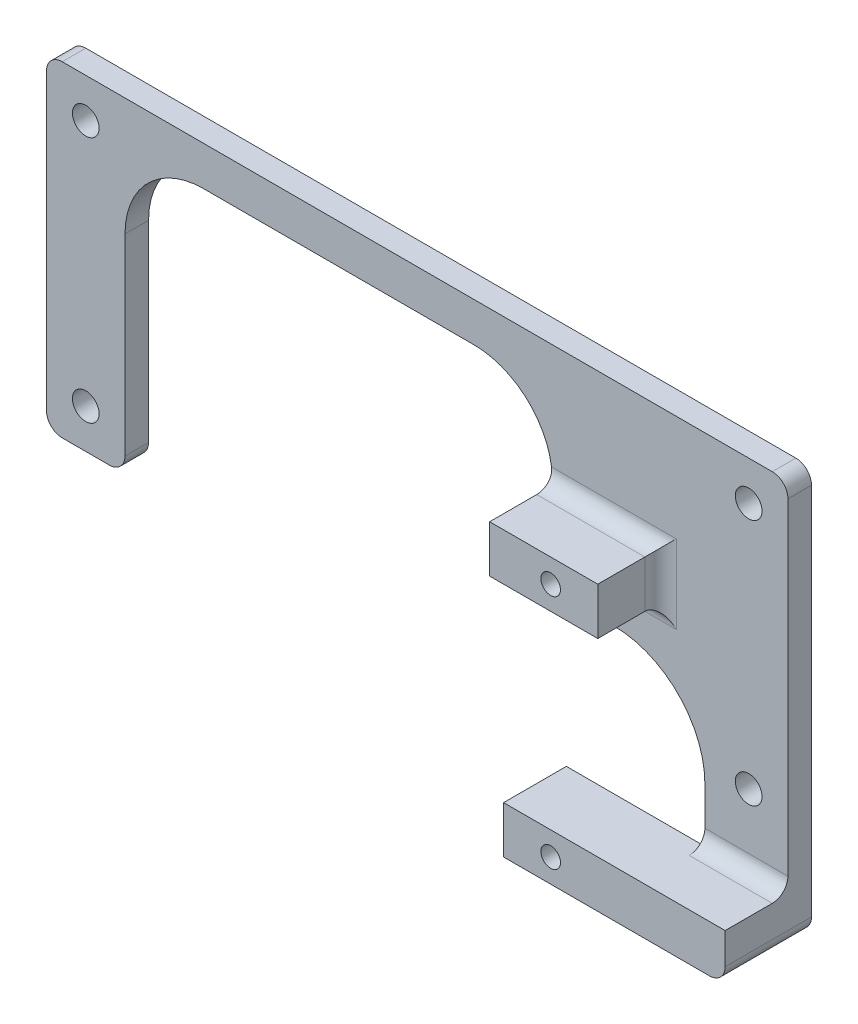
SolidWorks part; units mm, degrees
ref_plane "Front Plane" through (0, 0, 0) normal (0, 0, 1) x (1, 0, 0)
ref_plane "Top Plane" through (0, 0, 0) normal (0, 1, 0) x (1, 0, 0)
ref_plane "Right Plane" through (0, 0, 0) normal (1, 0, 0) x (0, 0, -1)
sketch "Sketch1" plane through (0, 0, 0) normal (0, 0, 1) x (1, 0, 0)
  line L0 (23.4746, -31.0442) -> (23.4746, 7.8468)
  line L1 (-40.9754, 12.8468) -> (53.4746, 12.8468)
  line L2 (-40.9754, 12.8468) -> (-40.9754, -28.6532)
  line L3 (-40.9754, -28.6532) -> (53.4746, -28.6532)
  line L4 (53.4746, 12.8468) -> (53.4746, -28.6532)
  line L5 (23.4746, -31.0442) -> (-30.9754, -31.0442)
  line L6 (23.4746, 7.8468) -> (-30.9754, 7.8468)
  line L7 (-30.9754, -31.0442) -> (-30.9754, 7.8468)
  line L8 (23.4746, -31.0442) -> (-30.9754, 7.8468) construction
  line L9 (23.4746, 7.8468) -> (-30.9754, -31.0442) construction
  line L10 (53.4746, 10.8468) -> (53.4746, -26.6532) construction
  line L11 (-40.9754, -26.6532) -> (-40.9754, 10.8468) construction
  point P5 (-3.7504, -11.5987)
  dimension "D1" = 0
  dimension "D2" = 41.5
  dimension "D3" = 5
  dimension "D4" = 30
  dimension "D5" = 10
  dimension "D6" = 0
extrude "Boss-Extrude1" add sketch "Sketch1" along normal blind 3 contours L3 L7 L6 L0 L4 L1 L2
fillet "Fillet1" radius 10 2 edges at (23.4746, 7.8468, 1.5) (-30.9754, 7.8468, 1.5)
sketch "Sketch2" plane through (0, 0, 0) normal (0, 0, -1) x (-1, 0, 0)
  line L0 (40.9754, 12.8468) -> (40.9754, -28.6532) construction
  line L1 (-53.4746, 12.8468) -> (-53.4746, -28.6532) construction
  line L2 (40.9754, 12.8468) -> (-53.4746, 12.8468) construction
  line L3 (-53.4746, 12.8468) -> (-53.4746, -28.6532) construction
  line L4 (-23.4746, -28.6532) -> (-53.4746, -28.6532) construction
  point P0 (-48.4746, 7.8468)
  point P1 (35.9754, -23.6532)
  point P4 (-48.4746, -23.6532)
  point P11 (35.9754, 7.8468)
  dimension "D1" = 5
  dimension "D2" = 5
  dimension "D3" = 5
  dimension "D4" = 5
  dimension "D5" = 5
  dimension "D6" = 5
  dimension "D7" = 5
  dimension "D8" = 5
hole_wizard "M3 Clearance Hole1" positions "Sketch3" profile "Sketch4" hole size "M3" standard "ANSI Metric" end condition through all
sketch "Sketch3" plane through (0, 0, 0) normal (0, 0, -1) x (-1, 0, 0)
  point P0 (-48.4746, 7.8468)
  point P6 (35.9754, -23.6532)
  point P9 (35.9754, 7.8468)
  point P17 (-48.4746, -23.6532)
  point P20 (-29.4675, -37.9659)
  point P22 (-48.4746, -23.6532)
  point P24 (-48.4746, -23.6532)
sketch "Sketch4" plane through (48.4746, 7.8468, 0) normal (1, 0, 0) x (0, 1, 0)
  line L0 (0, 0) -> (0, 3)
  line L1 (0, 3) -> (1.7, 3)
  line L2 (1.7, 3) -> (1.7, 0)
  line L5 (1.7, 0) -> (0, 0)
  line L11 (0, -6.35) -> (0, 107.95) construction
  dimension "Thru Hole Dia." = 3.4
  dimension "Thru Hole Depth" = 3
sketch "Sketch5" plane through (0, 0, 3) normal (0, 0, 1) x (1, 0, 0)
  line L4 (31.2496, -14.2567) -> (23.4746, -14.2567)
  line L5 (23.4746, -28.6532) -> (23.4746, -2.1532) construction
  line L6 (23.4746, -14.2567) -> (23.4746, -17.232)
  line L9 (42.896, -25.9032) -> (42.896, -28.6532)
  line L10 (23.4746, -28.6532) -> (53.4746, -28.6532) construction
  line L11 (42.896, -28.6532) -> (42.5667, -28.6532)
  circle A1 centre (31.2496, -25.9032) radius 11.6464
  circle A3 centre (6.2496, -7.9032) radius 6.35 construction
  point P0 (31.2496, -25.9032)
  dimension "D1" = 25
  dimension "D2" = 18
extrude "Cut-Extrude1" cut sketch "Sketch5" against normal through all
sketch "Sketch7" plane through (0, 0, 3) normal (0, 0, 1) x (1, 0, 0)
  line L0 (37.2496, -4.7282) -> (37.2496, -9.2282) construction
  line L1 (23.4746, -2.6782) -> (37.2496, -2.6782)
  line L2 (23.4746, -2.6782) -> (23.4746, -8.6782)
  line L3 (23.4746, -8.6782) -> (37.2496, -8.6782)
  line L4 (37.2496, -2.6782) -> (37.2496, -8.6782)
  line L5 (25.2496, -36.7282) -> (25.2496, -32.2282) construction
  line L6 (23.4746, -14.2567) -> (23.4746, -2.1532) construction
  line L8 (53.4746, -38.7782) -> (25.2496, -38.7782)
  line L9 (53.4746, -38.7782) -> (53.4746, -32.7782)
  line L10 (53.4746, -32.7782) -> (25.2496, -32.7782)
  line L11 (25.2496, -38.7782) -> (25.2496, -32.7782)
  line L12 (53.4746, 12.8468) -> (53.4746, -28.6532) construction
  arc A0 (32.5534, -37.2282) -> (29.9457, -37.2282) centre (31.2496, -35.7782) ccw construction
  arc A1 (29.9457, -4.2282) -> (32.5534, -4.2282) centre (31.2496, -5.6782) ccw construction
  dimension "D1" = 3
  dimension "D4" = 3
  dimension "D5" = 3
  dimension "D2" = 3
  dimension "D3" = 0
  dimension "D6" = 0
  dimension "D7" = 0
extrude "Boss-Extrude2" add sketch "Sketch7" against normal up to surface (8 mm away) from surface
sketch "Sketch15" plane through (0, -28.6532, 0) normal (0, -1, 0) x (1, 0, 0)
  line L1 (42.896, 0) -> (53.4746, 0)
  line L2 (42.896, 0) -> (42.896, 3)
  line L3 (42.896, 3) -> (53.4746, 3)
  line L4 (53.4746, 0) -> (53.4746, 3)
extrude "Boss-Extrude3" add sketch "Sketch15" along normal up to surface (10.125 mm away) up to face at (39.3621, -38.7782, 7)
sketch "Sketch14" plane through (0, 0, 3) normal (0, 0, -1) x (-1, 0, 0)
  line L1 (-42.896, -38.7782) -> (-37.2496, -38.7782)
  line L2 (-42.896, -38.7782) -> (-42.896, -32.7782)
  line L3 (-42.896, -32.7782) -> (-37.2496, -32.7782)
  line L4 (-37.2496, -38.7782) -> (-37.2496, -32.7782)
  line L5 (-37.2496, -38.7782) -> (-37.2496, -18.6532)
  line L6 (-42.896, -25.9032) -> (-42.896, -38.7782)
  line L7 (-42.896, -25.9032) -> (-42.896, -38.7782)
  line L8 (-37.2496, -18.6532) -> (-40.3642, -18.6532)
  arc A3 (-31.2496, -14.2567) -> (-42.896, -25.9032) centre (-31.2496, -25.9032) ccw
  arc A4 (-31.2496, -14.2567) -> (-42.896, -25.9032) centre (-31.2496, -25.9032) ccw
  dimension "D1" = 0
fillet "Fillet2" radius 2 10 edges at (30.3621, -8.6782, 3) (37.2496, -5.6782, 3) (30.3621, -2.6782, 3) (48.1853, -32.7782, 3) (23.4746, -14.2567, 1.5) (-40.9754, 12.8468, 1.5) (-30.9754, -28.6532, 1.5) (-40.9754, -28.6532, 1.5) (53.4746, -38.7782, 5.5) (53.4746, 12.8468, 1.5)
hole_wizard "Tap Drill for M3x0.5 Tap1" positions "Sketch18" profile "Sketch17" hole size "M3x0.5" standard "ANSI Metric" end condition through all
sketch "Sketch18" plane through (0, 0, 11) normal (0, 0, 1) x (1, 0, 0)
  point P0 (31.2496, -35.7782)
  point P3 (31.2496, -5.6782)
sketch "Sketch17" plane through (31.2496, -35.7782, 11) normal (1, 0, 0) x (0, -1, 0)
  line L0 (0, 0) -> (0, 11)
  line L1 (0, 11) -> (1.25, 11)
  line L2 (1.25, 11) -> (1.25, 0)
  line L5 (1.25, 0) -> (0, 0)
  line L11 (0, -6.35) -> (0, 107.95) construction
  dimension "Thru Hole Dia." = 2.5
  dimension "Thru Hole Depth" = 11
